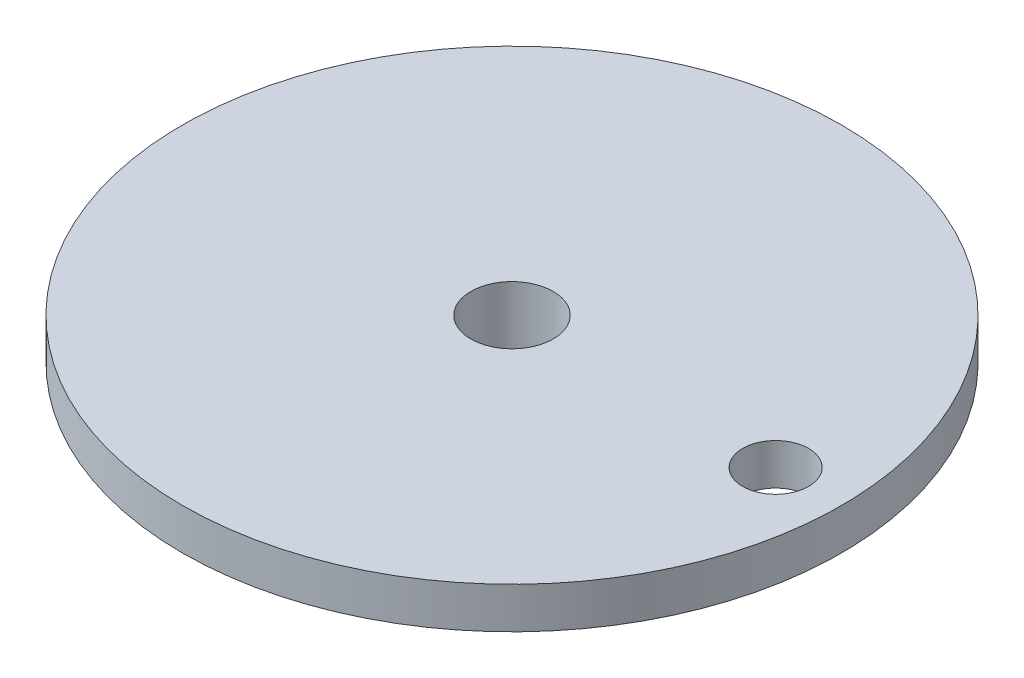
SolidWorks part; units mm, degrees
ref_plane "Front Plane" through (0, 0, 0) normal (0, 0, 1) x (1, 0, 0)
ref_plane "Top Plane" through (0, 0, 0) normal (0, 1, 0) x (1, 0, 0)
ref_plane "Right Plane" through (0, 0, 0) normal (1, 0, 0) x (0, 0, -1)
sketch "Sketch1" plane through (0, 0, 0) normal (0, 1, 0) x (1, 0, 0)
  circle A0 centre (0, 0) radius 40
  dimension "D1" = 80
extrude "Boss-Extrude1" add sketch "Sketch1" along normal blind 5
sketch "Sketch2" plane through (0, 0, 0) normal (0, -1, 0) x (1, 0, 0)
  circle A0 centre (0, 0) radius 11
  dimension "D1" = 22
extrude "Boss-Extrude2" add sketch "Sketch2" along normal blind 5
sketch "Sketch3" plane through (0, -5, 0) normal (0, -1, 0) x (1, 0, 0)
  circle A0 centre (0, 0) radius 5
  dimension "D1" = 10
extrude "Cut-Extrude1" cut sketch "Sketch3" against normal through all
sketch "Sketch4" plane through (0, 0, 0) normal (0, -1, 0) x (1, 0, 0)
  circle A0 centre (32, 0) radius 4
  point P2 (0, 0)
  dimension "D2" = 8
  dimension "D1" = 32
extrude "Cut-Extrude2" cut sketch "Sketch4" against normal through all
